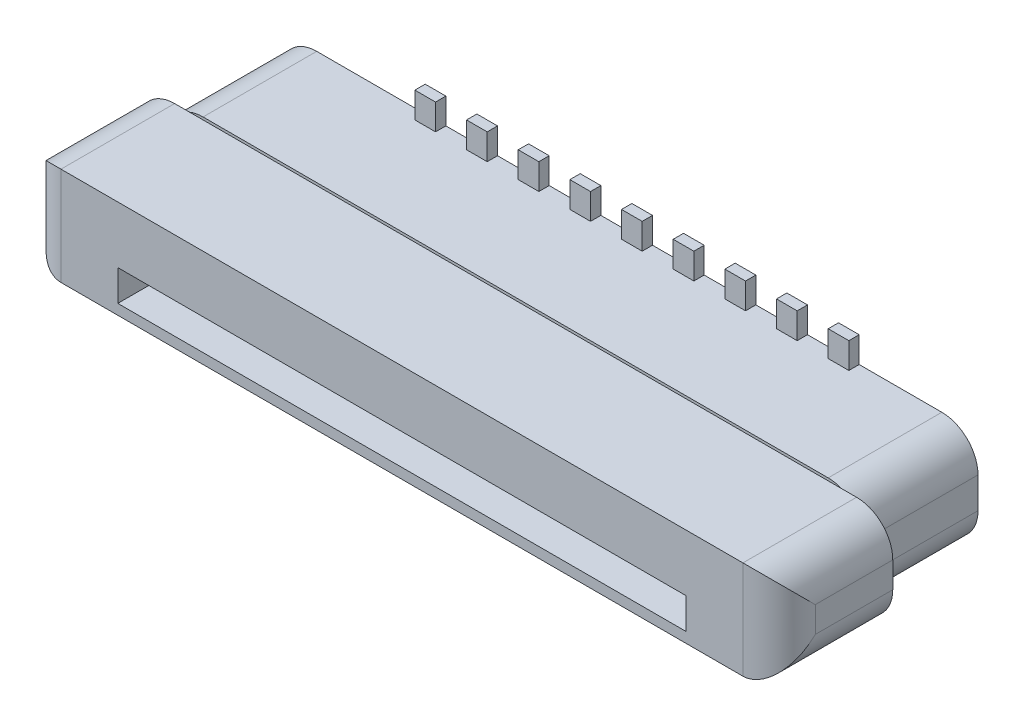
SolidWorks part; units mm, degrees
ref_plane "Top Plane" through (0, 0, 0) normal (0, 0, 1) x (1, 0, 0)
ref_plane "Right Plane" through (0, 0, 0) normal (0, 1, 0) x (1, 0, 0)
ref_plane "Front Plane" through (0, 0, 0) normal (1, 0, 0) x (0, 0, -1)
sketch "Sketch1" plane through (0, 0, 0) normal (0, 0, 1) x (1, 0, 0)
  line L1 (-6.75, -1) -> (6.75, -1)
  line L2 (-6.75, -1) -> (-6.75, 1)
  line L3 (-6.75, 1) -> (6.75, 1)
  line L4 (6.75, -1) -> (6.75, 1)
  line L5 (-6.75, -1) -> (6.75, 1) construction
  line L6 (-6.75, 1) -> (6.75, -1) construction
  point P0 (0, 0)
  dimension "D1" = 2
  dimension "D2" = 13.5
extrude "Boss-Extrude1" add sketch "Sketch1" along normal blind 2.2
fillet "Fillet1" radius 0.7 4 edges at (-6.75, 1, 1.1) (-6.75, -1, 1.1) (6.75, 1, 1.1) (6.75, -1, 1.1)
sketch "Sketch2" plane through (0, 0, 2.2) normal (0, 0, 1) x (1, 0, 0)
  line L0 (-6.05, -1) -> (6.05, -1) construction
  line L1 (7.3, -0.95) -> (-7.3, -0.95)
  line L2 (7.3, -0.95) -> (7.3, 0.95)
  line L3 (7.3, 0.95) -> (-7.3, 0.95)
  line L4 (-7.3, -0.95) -> (-7.3, 0.95)
  line L5 (7.3, -0.95) -> (-7.3, 0.95) construction
  line L6 (7.3, 0.95) -> (-7.3, -0.95) construction
  point P0 (0, 0)
  dimension "D1" = 0.05
  dimension "D2" = 14.6
extrude "Boss-Extrude2" add sketch "Sketch2" along normal offset from surface (2.2 mm away) 4.4 up to face at (0, 0, 0)
fillet "Fillet2" radius 0.7 6 edges at (-7.3, 0, 4.4) (7.3, 0, 4.4) (-7.3, 0.95, 3.3) (-7.3, -0.95, 3.3) (7.3, 0.95, 3.3) (7.3, -0.95, 3.3)
sketch "Sketch3" plane through (0, 0, 4.4) normal (0, 0, 1) x (1, 0, 0)
  line L0 (6.6, -0.95) -> (-6.6, -0.95) construction
  line L1 (-5.5, -0.75) -> (5.5, -0.75)
  line L2 (-5.5, -0.75) -> (-5.5, -0.15)
  line L3 (-5.5, -0.15) -> (5.5, -0.15)
  line L4 (5.5, -0.75) -> (5.5, -0.15)
  line L5 (0, 0) -> (0, -0.15) construction
  point P9 (-0.1028, -0.2)
  dimension "D1" = 0.6
  dimension "D2" = 0.2
  dimension "D3" = 11
extrude "Cut-Extrude1" cut sketch "Sketch3" against normal blind 4
sketch "Sketch4" plane through (0, 0, 0) normal (0, 0, -1) x (-1, 0, 0)
  line L0 (-6.05, 1) -> (6.05, 1) construction
  line L1 (4.45, 1) -> (4.05, 1)
  line L2 (4.45, 1) -> (4.45, -1.5)
  line L3 (4.45, -1.5) -> (4.05, -1.5)
  line L4 (4.05, 1) -> (4.05, -1.5)
  line L5 (3.45, 1) -> (3.45, -1.5)
  line L6 (3.45, 1) -> (3.05, 1)
  line L7 (3.05, 1) -> (3.05, -1.5)
  line L8 (3.45, -1.5) -> (3.05, -1.5)
  line L9 (2.45, 1) -> (2.45, -1.5)
  line L10 (2.45, 1) -> (2.05, 1)
  line L11 (2.05, 1) -> (2.05, -1.5)
  line L12 (2.45, -1.5) -> (2.05, -1.5)
  line L13 (1.45, 1) -> (1.45, -1.5)
  line L14 (1.45, 1) -> (1.05, 1)
  line L15 (1.05, 1) -> (1.05, -1.5)
  line L16 (1.45, -1.5) -> (1.05, -1.5)
  line L17 (0.45, 1) -> (0.45, -1.5)
  line L18 (0.45, 1) -> (0.05, 1)
  line L19 (0.05, 1) -> (0.05, -1.5)
  line L20 (0.45, -1.5) -> (0.05, -1.5)
  line L21 (-0.55, 1) -> (-0.55, -1.5)
  line L22 (-0.55, 1) -> (-0.95, 1)
  line L23 (-0.95, 1) -> (-0.95, -1.5)
  line L24 (-0.55, -1.5) -> (-0.95, -1.5)
  line L25 (-1.55, 1) -> (-1.55, -1.5)
  line L26 (-1.55, 1) -> (-1.95, 1)
  line L27 (-1.95, 1) -> (-1.95, -1.5)
  line L28 (-1.55, -1.5) -> (-1.95, -1.5)
  line L29 (-2.55, 1) -> (-2.55, -1.5)
  line L30 (-2.55, 1) -> (-2.95, 1)
  line L31 (-2.95, 1) -> (-2.95, -1.5)
  line L32 (-2.55, -1.5) -> (-2.95, -1.5)
  line L33 (-3.55, 1) -> (-3.55, -1.5)
  line L34 (-3.55, 1) -> (-3.95, 1)
  line L35 (-3.95, 1) -> (-3.95, -1.5)
  line L36 (-3.55, -1.5) -> (-3.95, -1.5)
  line L38 (6.05, -1) -> (-6.05, -1) construction
  line L39 (3.95, -1) -> (3.55, -1)
  line L40 (3.95, -1) -> (3.95, 1.5)
  line L41 (3.95, 1.5) -> (3.55, 1.5)
  line L42 (3.55, -1) -> (3.55, 1.5)
  line L43 (4.05, -1.5) -> (3.45, -1.5) construction
  line L44 (3.75, -1) -> (3.75, -1.5) construction
  line L45 (2.95, -1) -> (2.95, 1.5)
  line L46 (2.95, -1) -> (2.55, -1)
  line L47 (2.55, -1) -> (2.55, 1.5)
  line L48 (2.95, 1.5) -> (2.55, 1.5)
  line L49 (1.95, -1) -> (1.95, 1.5)
  line L50 (1.95, -1) -> (1.55, -1)
  line L51 (1.55, -1) -> (1.55, 1.5)
  line L52 (1.95, 1.5) -> (1.55, 1.5)
  line L53 (0.95, -1) -> (0.95, 1.5)
  line L54 (0.95, -1) -> (0.55, -1)
  line L55 (0.55, -1) -> (0.55, 1.5)
  line L56 (0.95, 1.5) -> (0.55, 1.5)
  line L57 (-0.05, -1) -> (-0.05, 1.5)
  line L58 (-0.05, -1) -> (-0.45, -1)
  line L59 (-0.45, -1) -> (-0.45, 1.5)
  line L60 (-0.05, 1.5) -> (-0.45, 1.5)
  line L61 (-1.05, -1) -> (-1.05, 1.5)
  line L62 (-1.05, -1) -> (-1.45, -1)
  line L63 (-1.45, -1) -> (-1.45, 1.5)
  line L64 (-1.05, 1.5) -> (-1.45, 1.5)
  line L65 (-2.05, -1) -> (-2.05, 1.5)
  line L66 (-2.05, -1) -> (-2.45, -1)
  line L67 (-2.45, -1) -> (-2.45, 1.5)
  line L68 (-2.05, 1.5) -> (-2.45, 1.5)
  line L69 (-3.05, -1) -> (-3.05, 1.5)
  line L70 (-3.05, -1) -> (-3.45, -1)
  line L71 (-3.45, -1) -> (-3.45, 1.5)
  line L72 (-3.05, 1.5) -> (-3.45, 1.5)
  line L73 (-4.05, -1) -> (-4.05, 1.5)
  line L74 (-4.05, -1) -> (-4.45, -1)
  line L75 (-4.45, -1) -> (-4.45, 1.5)
  line L76 (-4.05, 1.5) -> (-4.45, 1.5)
  line L77 (0.05, 0) -> (-0.05, 0) construction
  point P7 (4.25, -1.5)
  point P82 (0, 0)
  dimension "D1" = 0.4
  dimension "D2" = 1.5
  dimension "D4" = 1
  dimension "D6" = 1
  dimension "D3" = 9
  dimension "D5" = 9
extrude "Boss-Extrude3" add sketch "Sketch4" against normal blind 0.2
